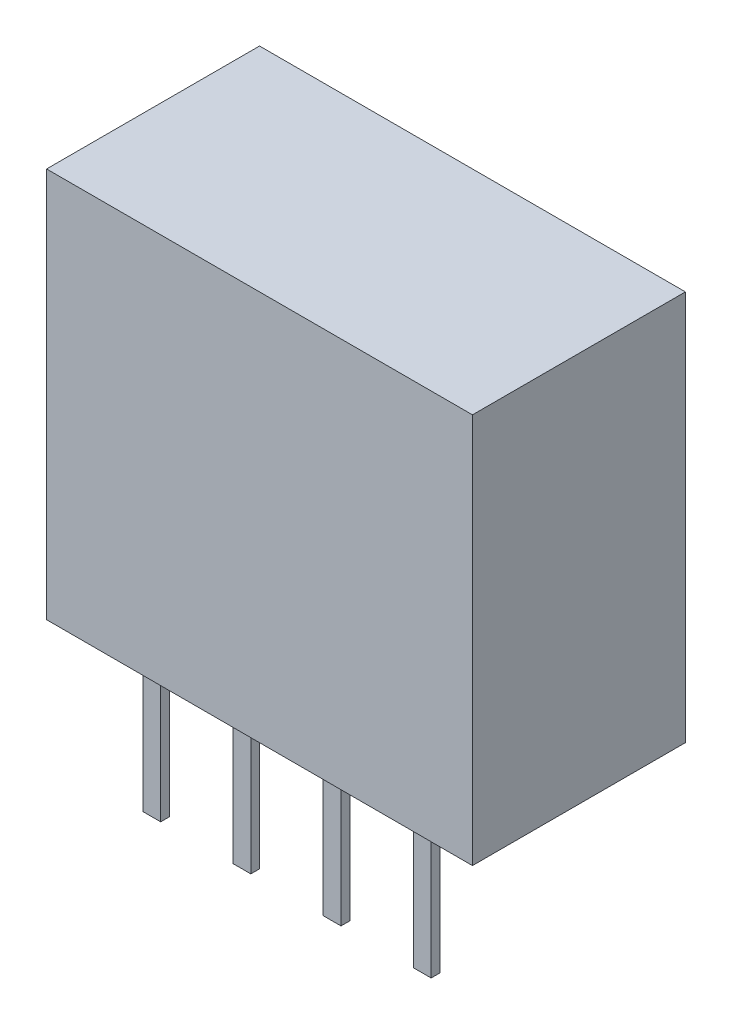
SolidWorks part; units mm, degrees
ref_plane "Front Plane" through (0, 0, 0) normal (0, 0, 1) x (1, 0, 0)
ref_plane "Top Plane" through (0, 0, 0) normal (0, 1, 0) x (1, 0, 0)
ref_plane "Right Plane" through (0, 0, 0) normal (1, 0, 0) x (0, 0, -1)
sketch "Sketch1" plane through (0, 0, 0) normal (0, 0, 1) x (1, 0, 0)
  line L1 (-6, 5.5) -> (6, 5.5)
  line L2 (-6, 5.5) -> (-6, -5.5)
  line L3 (-6, -5.5) -> (6, -5.5)
  line L4 (6, 5.5) -> (6, -5.5)
  line L5 (-6, 5.5) -> (6, -5.5) construction
  line L6 (-6, -5.5) -> (6, 5.5) construction
  point P0 (0, 0)
  dimension "D1" = 12
  dimension "D2" = 11
extrude "Boss-Extrude1" add sketch "Sketch1" along normal blind 6
sketch "Sketch2" plane through (0, -5.5, 0) normal (0, -1, 0) x (1, 0, 0)
  line L0 (-6, 5.1) -> (6, 5.1) construction
  line L1 (-6, 6) -> (-6, 0) construction
  line L2 (6, 6) -> (6, 0) construction
  line L3 (-6, 6) -> (6, 6) construction
  line L4 (1.02, 4.975) -> (1.52, 4.975)
  line L5 (3.56, 5.225) -> (4.06, 5.225)
  line L6 (3.56, 5.225) -> (3.56, 4.975)
  line L7 (3.56, 4.975) -> (4.06, 4.975)
  line L8 (4.06, 5.225) -> (4.06, 4.975)
  line L9 (3.56, 5.225) -> (4.06, 4.975) construction
  line L10 (3.56, 4.975) -> (4.06, 5.225) construction
  line L11 (1.52, 5.225) -> (1.52, 4.975)
  line L12 (1.02, 5.225) -> (1.52, 5.225)
  line L13 (1.02, 5.225) -> (1.02, 4.975)
  line L14 (1.02, 5.225) -> (1.52, 4.975) construction
  line L15 (1.02, 4.975) -> (1.52, 5.225) construction
  line L16 (-1.52, 4.975) -> (-1.02, 4.975)
  line L17 (-1.02, 5.225) -> (-1.02, 4.975)
  line L18 (-1.52, 5.225) -> (-1.02, 5.225)
  line L19 (-1.52, 5.225) -> (-1.52, 4.975)
  line L20 (-1.52, 5.225) -> (-1.02, 4.975) construction
  line L21 (-1.52, 4.975) -> (-1.02, 5.225) construction
  line L22 (-4.06, 4.975) -> (-3.56, 4.975)
  line L23 (-3.56, 5.225) -> (-3.56, 4.975)
  line L24 (-4.06, 5.225) -> (-3.56, 5.225)
  line L25 (-4.06, 5.225) -> (-4.06, 4.975)
  line L26 (-4.06, 5.225) -> (-3.56, 4.975) construction
  line L27 (-4.06, 4.975) -> (-3.56, 5.225) construction
  point P8 (3.81, 5.1)
  point P15 (1.27, 5.1)
  point P20 (-1.27, 5.1)
  point P25 (-3.81, 5.1)
  dimension "D1" = 0.9
  dimension "D2" = 0.5
  dimension "D3" = 0.25
  dimension "D4" = 2.19
  dimension "D6" = 4.73
  dimension "D7" = 0.9
  dimension "D5" = 4
extrude "Boss-Extrude2" add sketch "Sketch2" along normal blind 4.1
